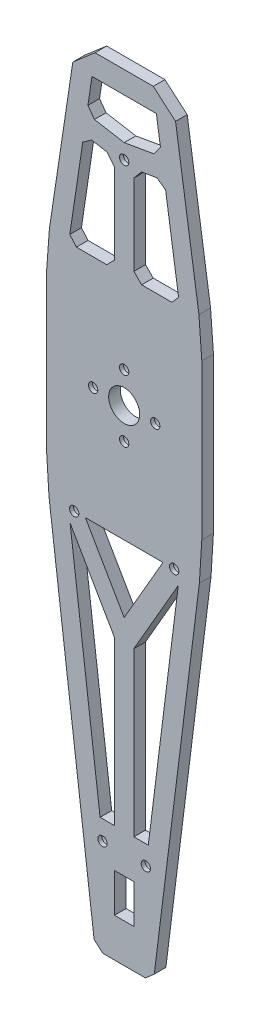
SolidWorks part; units mm, degrees
ref_plane "Front" through (0, 0, 0) normal (0, 0, 1) x (1, 0, 0)
ref_plane "Top" through (0, 0, 0) normal (0, 1, 0) x (1, 0, 0)
ref_plane "Right" through (0, 0, 0) normal (1, 0, 0) x (0, 0, -1)
sketch "草图1" plane through (0, 0, 0) normal (0, 0, 1) x (1, 0, 0)
  line L0 (20, 5) -> (20, 45)
  line L1 (-7.5, 100) -> (-13.2417, 95.0553)
  line L2 (-13.2417, 95.0553) -> (-19.2583, 54.9447)
  line L3 (7.5, 100) -> (13.2417, 95.0553)
  line L4 (-20, 5) -> (-20, 45)
  line L5 (7.5, 100) -> (-7.5, 100)
  line L6 (13.2417, 95.0553) -> (19.2583, 54.9447)
  line L7 (-19.2583, 54.9447) -> (-20, 45)
  line L8 (5.5, -100) -> (-5.5, -100)
  line L9 (-7.7481, -98.0154) -> (-19.3798, -4.9614)
  line L10 (19.3798, -4.9614) -> (7.7481, -98.0154)
  line L11 (19.2583, 54.9447) -> (20, 45)
  line L12 (-19.3798, -4.9614) -> (-20, 5)
  line L13 (19.3798, -4.9614) -> (20, 5)
  line L14 (-5.5, -100) -> (-7.7481, -98.0154)
  line L15 (7.7481, -98.0154) -> (5.5, -100)
  point P1 (-20, 50)
  point P3 (-20, 0)
  point P5 (20, 0)
  point P6 (20, 50)
  point P8 (12.5, 100)
  point P9 (-12.5, 100)
  point P10 (7.5, -100)
  point P12 (-7.5, -100)
extrude "凸台-拉伸1" add sketch "草图1" along normal blind 3
sketch "草图2" plane through (0, 0, 3) normal (0, 0, 1) x (1, 0, 0)
  line L0 (0, 0) -> (0, -100) construction
  line L1 (-5.5, -100) -> (5.5, -100) construction
  line L2 (10, -5) -> (-10, -5)
  line L3 (-10, -5) -> (0, -22.3205)
  line L4 (0, -22.3205) -> (10, -5)
  line L5 (-5.5, -100) -> (5.5, -100) construction
  line L12 (2.7867, -97.3953) -> (14.4184, -4.3412)
  line L13 (6.2111, -70) -> (13.9389, -8.1777)
  line L14 (-13.9389, -8.1777) -> (-2.5, -27.9904)
  line L15 (-14.4184, -4.3412) -> (-2.7867, -97.3953)
  line L16 (-13.9389, -8.1777) -> (-6.2111, -70)
  line L17 (2.5, -27.9904) -> (13.9389, -8.1777)
  line L18 (6.2111, -70) -> (2.5, -70)
  line L19 (2.5, -27.9904) -> (2.5, -70)
  line L20 (2.5, 0) -> (2.5, -100) construction
  line L21 (4.3301, -24.8205) -> (14.3301, -7.5) construction
  line L22 (10, -70) -> (-10, -70) construction
  line L23 (-2.5, -27.9904) -> (-2.5, -70)
  line L24 (-14.3301, -7.5) -> (-4.3301, -24.8205) construction
  line L25 (-2.5, -70) -> (-6.2111, -70)
  line L26 (2.5, -90) -> (2.5, -80)
  line L27 (2.5, -90) -> (-2.5, -90)
  line L29 (2.5, -80) -> (-2.5, -80)
  line L30 (-2.5, -90) -> (-2.5, -80)
  point P8 (0, -5)
  point P34 (0, -90)
  point P35 (0, -80)
  dimension "D1" = 5
  dimension "D2" = 5
  dimension "D9" = 10
  dimension "D3" = 5
  dimension "D4" = 5
  dimension "D5" = 5
  dimension "D6" = 65
  dimension "D7" = 2.5
  dimension "D8" = 5
extrude "切除-拉伸1" cut sketch "草图2" against normal up to next
sketch "草图3" plane through (0, 0, 0) normal (0, 0, -1) x (-1, 0, 0)
  point P0 (-5.5861, -75)
  point P1 (5.5861, -75)
hole_wizard "M2 凹头盖螺钉的柱形沉头孔1" positions "3D草图1" profile "草图4" counterbore size "M2" standard "ANSI Metric" end condition through all
sketch3d "3D草图1"
  point P0 (5.5861, -75, 0)
  point P3 (-5.5861, -75, 0)
sketch "草图4" plane through (5.5861, -75, 0) normal (1, 0, 0) x (0, 1, 0)
  line L0 (0, 0) -> (0, 3)
  line L1 (0, 3) -> (1.2, 3)
  line L3 (1.2, 3) -> (1.2, 2)
  line L4 (1.2, 2) -> (2.2, 2)
  line L5 (2.2, 2) -> (2.2, 0)
  line L7 (2.2, 0) -> (0, 0)
  line L11 (0, -6.35) -> (0, 107.95) construction
  dimension "通孔孔直径" = 2.4
  dimension "通孔孔深度" = 3
  dimension "柱形沉头孔直径" = 4.4
  dimension "柱形沉头孔深度" = 2
sketch "草图5" plane through (0, 0, 0) normal (0, 0, -1) x (-1, 0, 0)
  line L0 (-20, 25) -> (20, 25) construction
  line L1 (-20, 5) -> (-20, 45) construction
  line L2 (20, 45) -> (20, 5) construction
  circle A0 centre (0, 25) radius 4
extrude "切除-拉伸2" cut sketch "草图5" against normal up to next
sketch "草图6" plane through (0, 0, 0) normal (0, 0, -1) x (-1, 0, 0)
  point P0 (-8, 25)
  point P1 (0, 33)
  point P2 (8, 25)
  point P3 (0, 17)
  point P4 (0, 25)
  dimension "D1" = 8
  dimension "D2" = 8
  dimension "D3" = 8
  dimension "D4" = 8
hole_wizard "M2 凹头盖螺钉的柱形沉头孔2" positions "3D草图2" profile "草图7" counterbore size "M2" standard "ANSI Metric" end condition through all
sketch3d "3D草图2"
  point P0 (8, 25, 0)
  point P3 (0, 33, 0)
  point P6 (-8, 25, 0)
  point P9 (0, 17, 0)
sketch "草图7" plane through (8, 25, 0) normal (1, 0, 0) x (0, 1, 0)
  line L0 (0, 0) -> (0, 3)
  line L1 (0, 3) -> (1.2, 3)
  line L3 (1.2, 3) -> (1.2, 2)
  line L4 (1.2, 2) -> (2.2, 2)
  line L5 (2.2, 2) -> (2.2, 0)
  line L7 (2.2, 0) -> (0, 0)
  line L11 (0, -6.35) -> (0, 107.95) construction
  dimension "通孔孔直径" = 2.4
  dimension "通孔孔深度" = 3
  dimension "柱形沉头孔直径" = 4.4
  dimension "柱形沉头孔深度" = 2
sketch "草图8" plane through (0, 0, 0) normal (0, 0, -1) x (-1, 0, 0)
  line L0 (0, -3.3014) -> (0, -6.7473) construction
  point P2 (12.88, -5.0117)
  point P12 (-12.88, -5.0117)
hole_wizard "M2 凹头盖螺钉的柱形沉头孔3" positions "3D草图3" profile "草图9" counterbore size "M2" standard "ANSI Metric" end condition through all
sketch3d "3D草图3"
  point P0 (12.88, -5.0117, 0)
  point P3 (-12.88, -5.0117, 0)
sketch "草图9" plane through (12.88, -5.0117, 0) normal (1, 0, 0) x (0, 1, 0)
  line L0 (0, 0) -> (0, 3)
  line L1 (0, 3) -> (1.2, 3)
  line L3 (1.2, 3) -> (1.2, 2)
  line L4 (1.2, 2) -> (2.2, 2)
  line L5 (2.2, 2) -> (2.2, 0)
  line L7 (2.2, 0) -> (0, 0)
  line L11 (0, -6.35) -> (0, 107.95) construction
  dimension "通孔孔直径" = 2.4
  dimension "通孔孔深度" = 3
  dimension "柱形沉头孔直径" = 4.4
  dimension "柱形沉头孔深度" = 2
sketch "草图10" plane through (0, 0, 0) normal (0, 0, -1) x (-1, 0, 0)
  line L0 (-9.5291, 85.3364) -> (-1.6465, 83.9709) construction
  line L1 (9.5291, 85.3364) -> (1.6465, 83.9709) construction
  line L2 (-14.3136, 54.203) -> (-8.297, 94.3136)
  line L3 (-14.0169, 56.1809) -> (-10.6793, 78.4319)
  line L4 (-9.344, 87.3336) -> (-8.297, 94.3136)
  line L5 (8.297, 94.3136) -> (14.3136, 54.203)
  line L6 (8.297, 94.3136) -> (9.344, 87.3336)
  line L7 (-8.297, 94.3136) -> (0, 94.3136)
  line L8 (-12.3136, 54.203) -> (-4.5, 54.203)
  line L9 (0, 95.3482) -> (0, 43.337) construction
  line L10 (-2.5, 77.0442) -> (-2.5, 56.203)
  line L11 (-9.344, 87.3336) -> (-7.6701, 85.0144)
  line L12 (9.344, 87.3336) -> (7.6701, 85.0144)
  line L13 (-10.3826, 80.4098) -> (-2.5, 79.0442) construction
  line L14 (-10.6793, 78.4319) -> (-8.4119, 80.0684)
  line L15 (4.5, 54.203) -> (12.3136, 54.203)
  line L16 (-8.4119, 80.0684) -> (-4.4706, 79.3856)
  line L17 (8.4119, 80.0684) -> (4.4706, 79.3856)
  line L18 (-7.6701, 85.0144) -> (0, 83.6856)
  line L19 (7.6701, 85.0144) -> (0, 83.6856)
  line L20 (0, 94.3136) -> (8.297, 94.3136)
  line L21 (-4.4706, 79.3856) -> (-2.5, 77.0442)
  line L22 (2.5, 77.0442) -> (2.5, 56.203)
  line L23 (10.6793, 78.4319) -> (14.0169, 56.1809)
  line L24 (10.3826, 80.4098) -> (2.5, 79.0442) construction
  line L25 (4.4706, 79.3856) -> (2.5, 77.0442)
  line L26 (10.6793, 78.4319) -> (8.4119, 80.0684)
  line L27 (-12.3136, 54.203) -> (-14.0169, 56.1809)
  line L28 (-4.5, 54.203) -> (-2.5, 56.203)
  line L29 (2.5, 56.203) -> (4.5, 54.203)
  line L30 (12.3136, 54.203) -> (14.0169, 56.1809)
  point P16 (-2.5, 54.203)
  point P17 (2.5, 54.203)
  point P18 (-10.3826, 80.4098)
  point P26 (-9.6407, 85.3557)
  point P28 (9.6407, 85.3557)
  dimension "D3" = 26.5
  dimension "D6" = 5
  dimension "D1" = 5
  dimension "D2" = 5
  dimension "D7" = 5
extrude "切除-拉伸3" cut sketch "草图10" against normal blind 3
sketch "草图11" plane through (0, 0, 0) normal (0, 0, -1) x (-1, 0, 0)
  point P11 (0, 79.8401)
hole_wizard "M2 凹头盖螺钉的柱形沉头孔5" positions "3D草图5" profile "草图13" counterbore size "M2" standard "ANSI Metric" end condition through all
sketch3d "3D草图5"
  point P0 (0, 79.8401, 0)
sketch "草图13" plane through (0, 79.8401, 0) normal (1, 0, 0) x (0, 1, 0)
  line L0 (0, 0) -> (0, 3)
  line L1 (0, 3) -> (1.2, 3)
  line L3 (1.2, 3) -> (1.2, 2)
  line L4 (1.2, 2) -> (2.2, 2)
  line L5 (2.2, 2) -> (2.2, 0)
  line L7 (2.2, 0) -> (0, 0)
  line L11 (0, -6.35) -> (0, 107.95) construction
  dimension "通孔孔直径" = 2.4
  dimension "通孔孔深度" = 3
  dimension "柱形沉头孔直径" = 4.4
  dimension "柱形沉头孔深度" = 2
